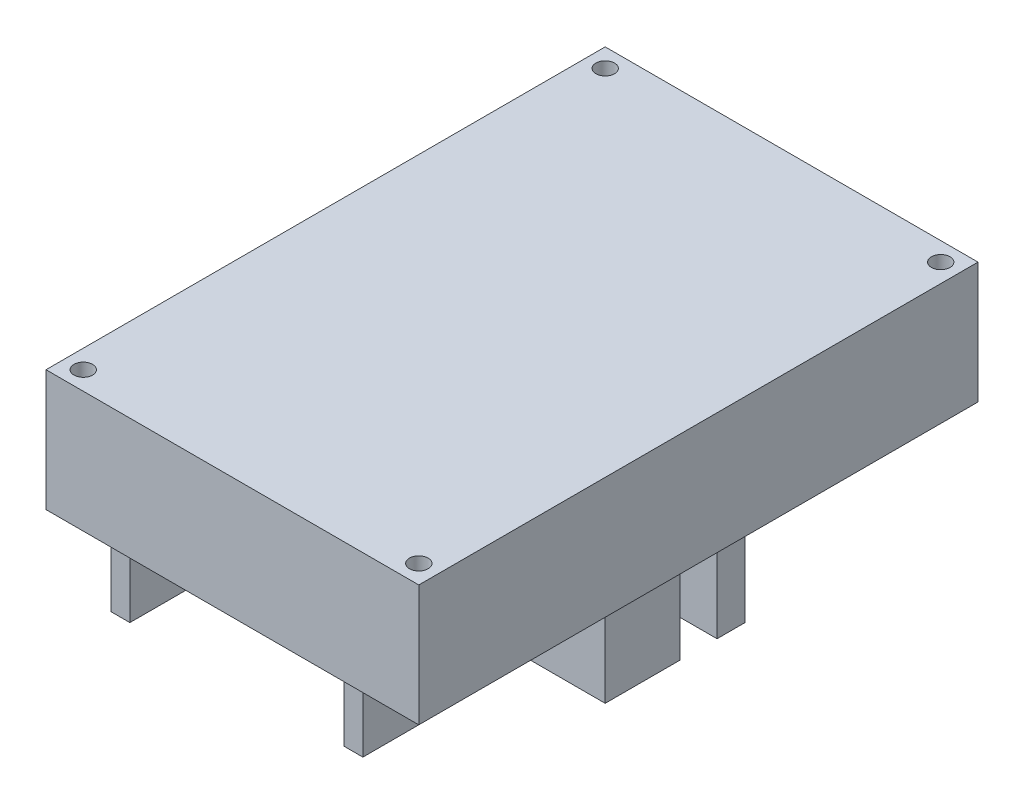
SolidWorks part; units mm, degrees
ref_plane "Plan de face" through (0, 0, 0) normal (0, 0, 1) x (1, 0, 0)
ref_plane "Plan de dessus" through (0, 0, 0) normal (0, 1, 0) x (1, 0, 0)
ref_plane "Plan de droite" through (0, 0, 0) normal (1, 0, 0) x (0, 0, -1)
sketch "Esquisse1" plane through (0, 0, 0) normal (0, 1, 0) x (1, 0, 0)
  line L0 (0, -55) -> (0, 55) construction
  line L1 (-20, -30) -> (20, -30)
  line L2 (-20, -30) -> (-20, 30)
  line L3 (-20, 30) -> (20, 30)
  line L4 (20, -30) -> (20, 30)
  line L5 (-20, -30) -> (20, 30) construction
  line L6 (-20, 30) -> (20, -30) construction
  line L7 (-55, 0) -> (55, 0) construction
  circle A0 centre (-18, 28) radius 1
  circle A1 centre (18, 28) radius 1
  circle A2 centre (18, -28) radius 1
  circle A3 centre (-18, -28) radius 1
  point P0 (0, 0)
  point P8 (0, 0)
  dimension "D5" = 2
  dimension "D1" = 40
  dimension "D2" = 60
  dimension "D3" = 2
  dimension "D4" = 2
extrude "Boss.-Extru.1" add sketch "Esquisse1" along normal mid plane 13
sketch "Esquisse3" plane through (0, -6.5, 0) normal (0, -1, 0) x (1, 0, 0)
  line L0 (-20, 30) -> (20, 30) construction
  line L1 (-17, 26) -> (-15, 26)
  line L2 (-17, 26) -> (-17, -21)
  line L3 (-17, -21) -> (-15, -21)
  line L4 (-15, 26) -> (-15, -21)
  line L5 (8, 26) -> (10, 26)
  line L6 (8, 26) -> (8, -21)
  line L7 (8, -21) -> (10, -21)
  line L8 (10, 26) -> (10, -21)
  line L9 (10, 8) -> (18, 8)
  line L10 (10, 8) -> (10, 0)
  line L11 (10, 0) -> (18, 0)
  line L12 (18, 8) -> (18, 0)
  line L17 (10, -4) -> (18, -4)
  line L18 (10, -4) -> (10, -7)
  line L19 (10, -7) -> (18, -7)
  line L20 (18, -4) -> (18, -7)
  line L21 (20, -30) -> (-20, -30) construction
  line L22 (-20, -30) -> (-20, 30) construction
  line L23 (20, 30) -> (20, -30) construction
  dimension "D1" = 4
  dimension "D2" = 9
  dimension "D3" = 3
  dimension "D4" = 2
  dimension "D5" = 2
  dimension "D6" = 27
  dimension "D7" = 2
  dimension "D8" = 8
  dimension "D9" = 22
  dimension "D10" = 23
  dimension "D11" = 3
  dimension "D12" = 8
extrude "Boss.-Extru.2" add sketch "Esquisse3" along normal blind 10 contours L12 L9 L8 L11 | L20 L17 L8 L19 | L8 L5 L6 L7 | L4 L1 L2 L3
